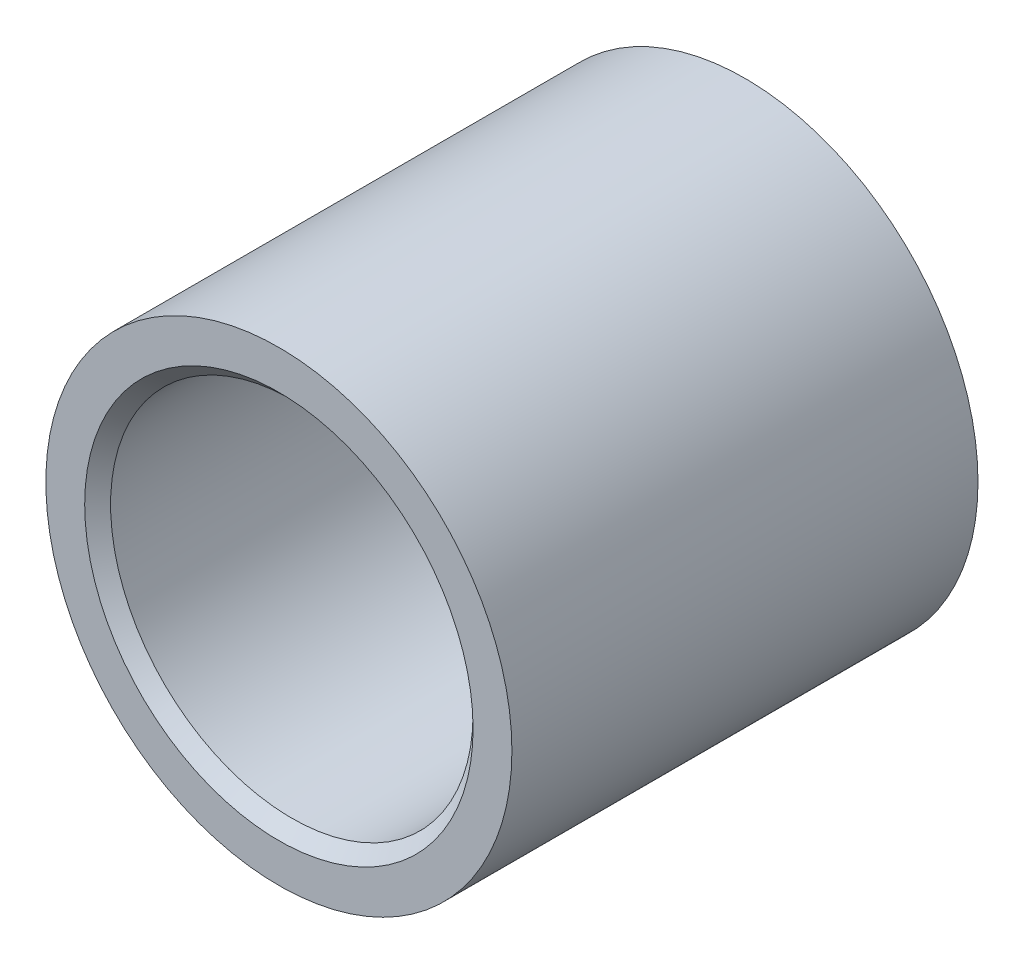
SolidWorks part; units mm, degrees
material "Brass"
ref_plane "Front Plane" through (0, 0, 0) normal (0, 0, 1) x (1, 0, 0)
ref_plane "Top Plane" through (0, 0, 0) normal (0, 1, 0) x (1, 0, 0)
ref_plane "Right Plane" through (0, 0, 0) normal (1, 0, 0) x (0, 0, -1)
sketch "Sketch1" plane through (0, 0, 0) normal (0, 0, 1) x (1, 0, 0)
  circle A0 centre (0, 0) radius 18
  circle A1 centre (0, 0) radius 14
  dimension "D1" = 36
  dimension "D2" = 28
extrude "Boss-Extrude1" add sketch "Sketch1" along normal mid plane 36
chamfer "Chamfer1" distance 1 angle 45 2 edges at (14, 0, -18) (14, 0, 18)
